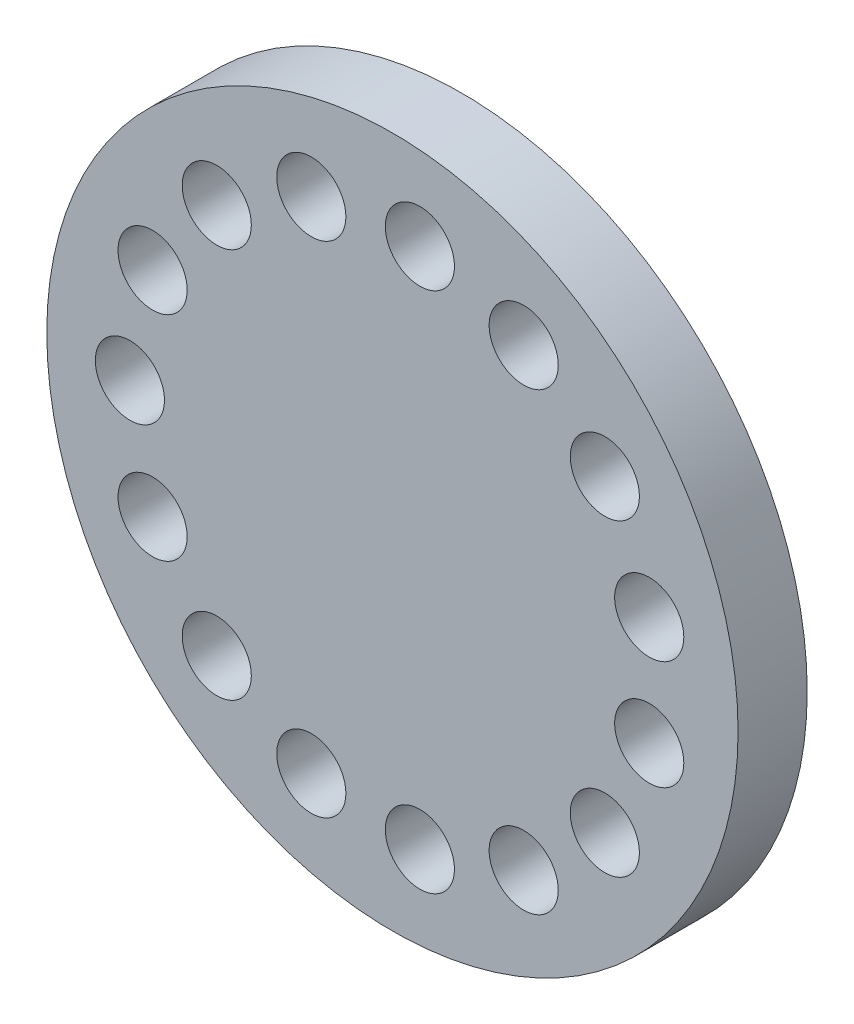
SolidWorks part; units mm, degrees
ref_plane "Alzado" through (0, 0, 0) normal (0, 0, 1) x (1, 0, 0)
ref_plane "Planta" through (0, 0, 0) normal (0, 1, 0) x (1, 0, 0)
ref_plane "Vista lateral" through (0, 0, 0) normal (1, 0, 0) x (0, 0, -1)
sketch "Croquis1" plane through (0, 0, 0) normal (0, 0, 1) x (1, 0, 0)
  line L0 (0, 0) -> (-37.9771, 0) construction
  circle A0 centre (0, 0) radius 50
  circle A1 centre (-37.9771, 0) radius 5
  circle A2 centre (-34.6938, 15.4467) radius 5
  circle A3 centre (-25.4116, 28.2225) radius 5
  circle A4 centre (-11.7356, 36.1184) radius 5
  circle A5 centre (3.9697, 37.7691) radius 5
  circle A6 centre (18.9885, 32.8891) radius 5
  circle A7 centre (30.7241, 22.3224) radius 5
  circle A8 centre (37.1472, 7.8959) radius 5
  circle A9 centre (37.1472, -7.8959) radius 5
  circle A10 centre (30.7241, -22.3224) radius 5
  circle A11 centre (18.9885, -32.8891) radius 5
  circle A12 centre (3.9697, -37.7691) radius 5
  circle A13 centre (-11.7356, -36.1184) radius 5
  circle A14 centre (-25.4116, -28.2225) radius 5
  circle A15 centre (-34.6938, -15.4467) radius 5
  point P36 (0, 0)
  dimension "D1" = 100
  dimension "D2" = 10
  dimension "D3" = 15
extrude "Saliente-Extruir1" add sketch "Croquis1" along normal blind 10
sketch "Croquis2" plane through (0, 0, 10) normal (0, 0, 1) x (1, 0, 0)
  circle A0 centre (0, 0) radius 12.5
  dimension "D1" = 25
